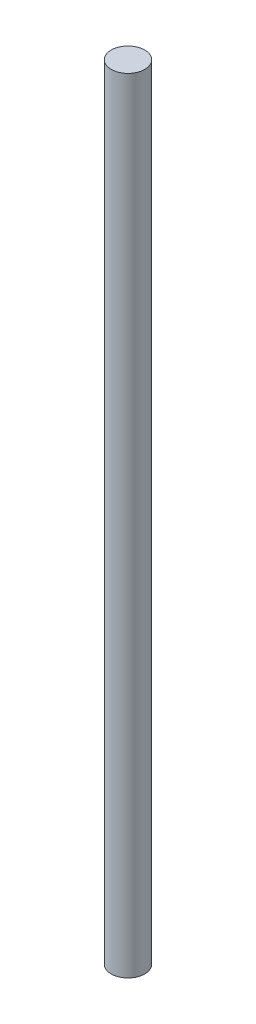
SolidWorks part; units mm, degrees
material "Hexcel AS4C (3000 Filaments)"
ref_plane "Front Plane" through (0, 0, 0) normal (0, 0, 1) x (1, 0, 0)
ref_plane "Top Plane" through (0, 0, 0) normal (0, 1, 0) x (1, 0, 0)
ref_plane "Right Plane" through (0, 0, 0) normal (1, 0, 0) x (0, 0, -1)
sketch "Sketch1" plane through (0, 0, 0) normal (0, 1, 0) x (1, 0, 0)
  circle A0 centre (0, 0) radius 15
  dimension "D1" = 30
extrude "Boss-Extrude1" add sketch "Sketch1" along normal blind 700
